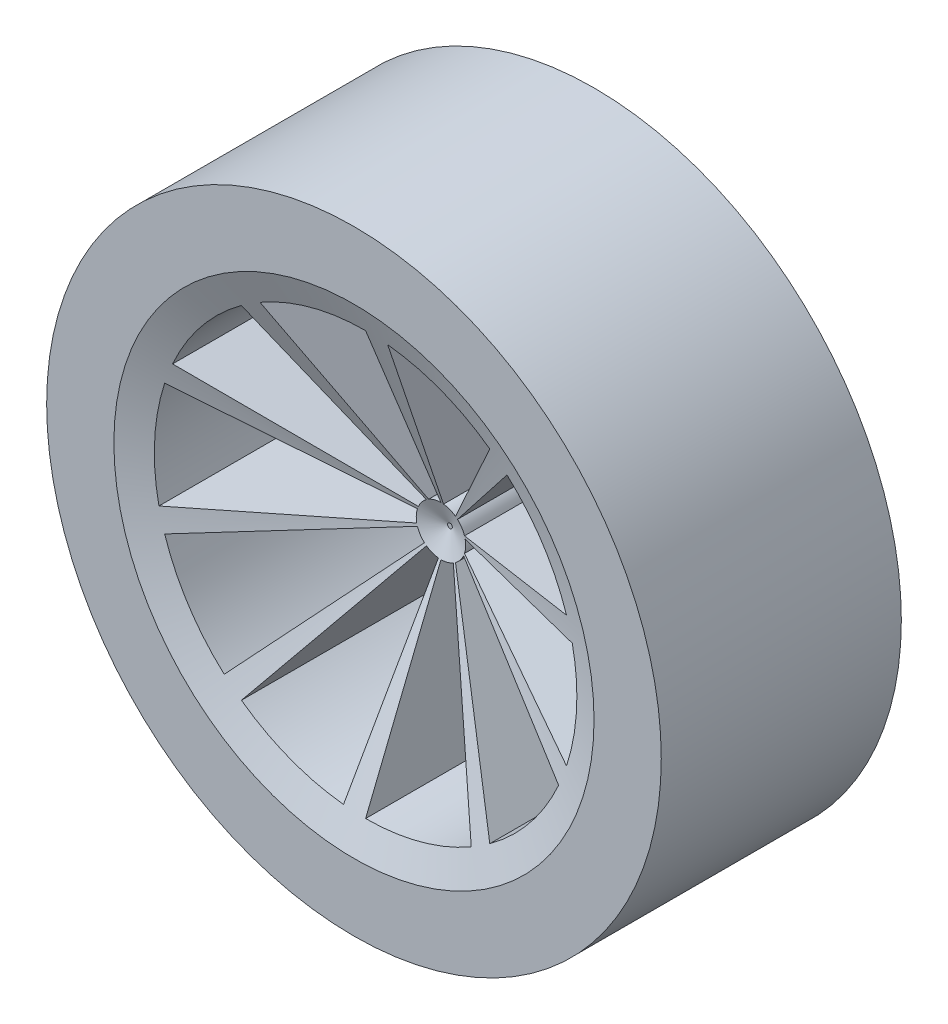
SolidWorks part; units mm, degrees
ref_plane "정면" through (0, 0, 0) normal (0, 0, 1) x (1, 0, 0)
ref_plane "윗면" through (0, 0, 0) normal (0, 1, 0) x (1, 0, 0)
ref_plane "우측면" through (0, 0, 0) normal (1, 0, 0) x (0, 0, -1)
sketch "스케치1" plane through (0, 0, 0) normal (0, 0, 1) x (1, 0, 0)
  circle A0 centre (0, 0) radius 32
  dimension "D1" = 64
extrude "보스-돌출1" add sketch "스케치1" along normal blind 25
sketch "스케치2" plane through (0, 0, 25) normal (0, 0, 1) x (1, 0, 0)
  circle A0 centre (0, 0) radius 25
  dimension "D1" = 50
extrude "컷-돌출1" cut sketch "스케치2" against normal blind 10 draft 68
sketch "스케치4" plane through (0, 0, 0) normal (0, 0, -1) x (-1, 0, 0)
  line L0 (0, 22) -> (0, 2.5751)
  line L1 (11, 19.0526) -> (1.2876, 2.2301)
  line L2 (20.098, 8.9482) -> (2.3525, 1.0474)
  line L3 (12.9313, 17.7984) -> (1.5136, 2.0833)
  line L4 (21.5192, -4.5741) -> (2.5189, -0.5354)
  line L5 (20.9232, 6.7984) -> (2.4491, 0.7958)
  line L6 (14.7209, -16.3492) -> (1.7231, -1.9137)
  line L7 (20.9232, -6.7984) -> (2.4491, -0.7958)
  line L8 (2.2996, -21.8795) -> (0.2692, -2.561)
  line L9 (12.9313, -17.7984) -> (1.5136, -2.0833)
  line L10 (-11, -19.0526) -> (-1.2876, -2.2301)
  line L11 (0, -22) -> (0, -2.5751)
  line L12 (-20.098, -8.9482) -> (-2.3525, -1.0474)
  line L13 (-12.9313, -17.7984) -> (-1.5136, -2.0833)
  line L14 (-21.5192, 4.5741) -> (-2.5189, 0.5354)
  line L15 (-20.9232, -6.7984) -> (-2.4491, -0.7958)
  line L16 (-14.7209, 16.3492) -> (-1.7231, 1.9137)
  line L17 (-20.9232, 6.7984) -> (-2.4491, 0.7958)
  line L18 (-2.2996, 21.8795) -> (-0.2692, 2.561)
  line L19 (-12.9313, 17.7984) -> (-1.5136, 2.0833)
  arc A1 (0, 22) -> (11, 19.0526) centre (0, 0) cw
  arc A2 (0, 2.5751) -> (1.2876, 2.2301) centre (0, 0) cw
  arc A3 (1.5136, 2.0833) -> (2.3525, 1.0474) centre (0, 0) cw
  arc A4 (12.9313, 17.7984) -> (20.098, 8.9482) centre (0, 0) cw
  arc A5 (2.4491, 0.7958) -> (2.5189, -0.5354) centre (0, 0) cw
  arc A6 (20.9232, 6.7984) -> (21.5192, -4.5741) centre (0, 0) cw
  arc A7 (2.4491, -0.7958) -> (1.7231, -1.9137) centre (0, 0) cw
  arc A8 (20.9232, -6.7984) -> (14.7209, -16.3492) centre (0, 0) cw
  arc A9 (1.5136, -2.0833) -> (0.2692, -2.561) centre (0, 0) cw
  arc A10 (12.9313, -17.7984) -> (2.2996, -21.8795) centre (0, 0) cw
  arc A11 (0, -2.5751) -> (-1.2876, -2.2301) centre (0, 0) cw
  arc A12 (0, -22) -> (-11, -19.0526) centre (0, 0) cw
  arc A13 (-1.5136, -2.0833) -> (-2.3525, -1.0474) centre (0, 0) cw
  arc A14 (-12.9313, -17.7984) -> (-20.098, -8.9482) centre (0, 0) cw
  arc A15 (-2.4491, -0.7958) -> (-2.5189, 0.5354) centre (0, 0) cw
  arc A16 (-20.9232, -6.7984) -> (-21.5192, 4.5741) centre (0, 0) cw
  arc A17 (-2.4491, 0.7958) -> (-1.7231, 1.9137) centre (0, 0) cw
  arc A18 (-20.9232, 6.7984) -> (-14.7209, 16.3492) centre (0, 0) cw
  arc A19 (-1.5136, 2.0833) -> (-0.2692, 2.561) centre (0, 0) cw
  arc A20 (-12.9313, 17.7984) -> (-2.2996, 21.8795) centre (0, 0) cw
  point P45 (0, 0)
  dimension "D1" = 10
extrude "컷-돌출6" cut sketch "스케치4" against normal blind 50
